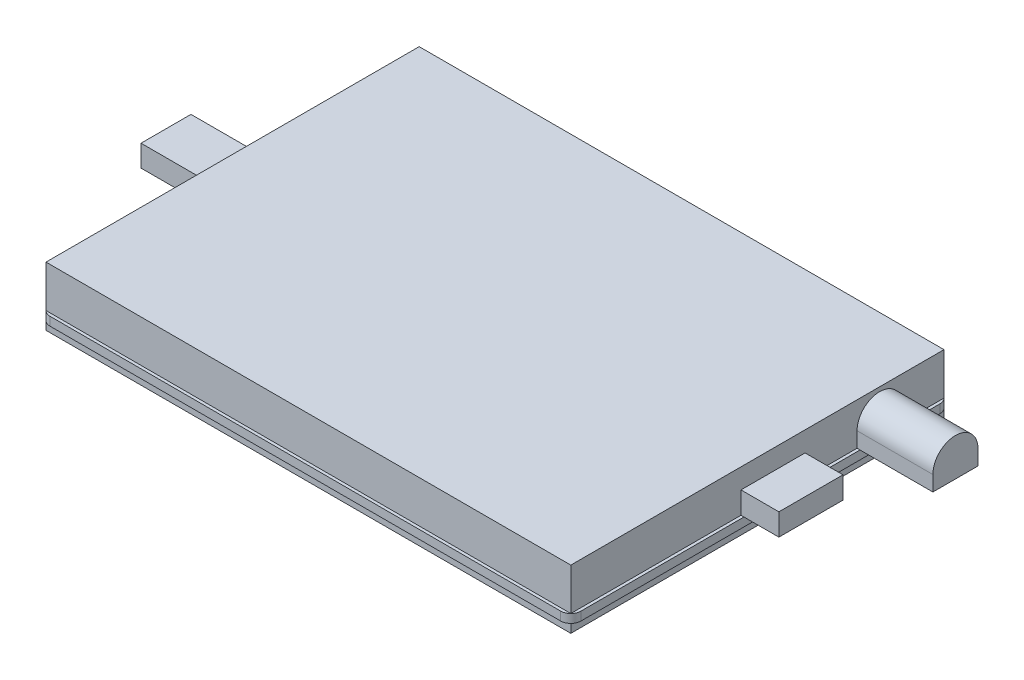
SolidWorks part; units mm, degrees
ref_plane "Plan de face" through (0, 0, 0) normal (0, 0, 1) x (1, 0, 0)
ref_plane "Plan de dessus" through (0, 0, 0) normal (0, 1, 0) x (1, 0, 0)
ref_plane "Plan de droite" through (0, 0, 0) normal (1, 0, 0) x (0, 0, -1)
sketch "Esquisse1" plane through (0, 0, 0) normal (0, 1, 0) x (1, 0, 0)
  line L1 (-50.5, -37.5) -> (50.5, -37.5)
  line L2 (-52.5, -35.5) -> (-52.5, 35.5)
  line L3 (-50.5, 37.5) -> (50.5, 37.5)
  line L4 (52.5, -35.5) -> (52.5, 35.5)
  line L5 (-52.5, -37.5) -> (52.5, 37.5) construction
  line L6 (-52.5, 37.5) -> (52.5, -37.5) construction
  arc A0 (50.5, 37.5) -> (52.5, 35.5) centre (50.5, 35.5) cw
  arc A1 (50.5, -37.5) -> (52.5, -35.5) centre (50.5, -35.5) ccw
  arc A2 (-50.5, -37.5) -> (-52.5, -35.5) centre (-50.5, -35.5) cw
  arc A3 (-52.5, 35.5) -> (-50.5, 37.5) centre (-50.5, 35.5) cw
  point P0 (0, 0)
  dimension "D3" = 2
  dimension "D1" = 75
  dimension "D2" = 105
extrude "FormePCB" add sketch "Esquisse1" along normal blind 1.7
sketch "Esquisse3" plane through (0, 0, 0) normal (0, 1, 0) x (1, 0, 0)
  line L0 (60.2106, 0) -> (-60.2106, 0) construction
  line L1 (0, 42.1093) -> (0, -42.1093) construction
  circle A0 centre (48, 33) radius 2
  circle A1 centre (48, -33) radius 2
  circle A2 centre (-48, 33) radius 2
  circle A3 centre (-48, -33) radius 2
  dimension "D3" = 4
  dimension "D1" = 33
  dimension "D2" = 48
extrude "PaternTrouPCB" cut sketch "Esquisse3" along normal through all
sketch "Esquisse4" plane through (0, 0, 0) normal (0, 1, 0) x (1, 0, 0)
  line L1 (-51.9142, -36.9142) -> (51.9142, -36.9142)
  line L2 (-51.9142, -36.9142) -> (-51.9142, 36.9142)
  line L3 (-51.9142, 36.9142) -> (51.9142, 36.9142)
  line L4 (51.9142, -36.9142) -> (51.9142, 36.9142)
  line L5 (-51.9142, -36.9142) -> (51.9142, 36.9142) construction
  line L6 (-51.9142, 36.9142) -> (51.9142, -36.9142) construction
  arc A0 (52.5, 35.5) -> (50.5, 37.5) centre (50.5, 35.5) ccw construction
  point P0 (0, 0)
extrude "EspaceComposante" add sketch "Esquisse4" along normal blind 10 and the other way blind 1.7 separate body
sketch "Esquisse5" plane through (51.9142, 0, 0) normal (1, 0, 0) x (0, 0, -1)
  line L1 (-3.2459, 6.0441) -> (9.4285, 6.0441)
  line L2 (-3.2459, 6.0441) -> (-3.2459, 1.7)
  line L3 (-3.2459, 1.7) -> (9.4285, 1.7)
  line L4 (9.4285, 6.0441) -> (9.4285, 1.7)
  line L13 (-35.5, 1.7) -> (35.5, 1.7) construction
extrude "EspaceSwitch" add sketch "Esquisse5" along normal blind 7.5
sketch "Esquisse6" plane through (51.9142, 0, 0) normal (1, 0, 0) x (0, 0, -1)
  line L0 (19.7174, 1.7) -> (28.6437, 1.7)
  line L1 (-35.5, 1.7) -> (35.5, 1.7) construction
  line L2 (28.6437, 1.7) -> (28.6437, 4.6993)
  line L3 (19.7174, 4.6993) -> (19.7174, 1.7)
  arc A0 (28.6437, 4.6993) -> (19.7174, 4.6993) centre (24.1806, 4.6993) ccw
extrude "EspacePower" add sketch "Esquisse6" along normal blind 15
sketch "Esquisse7" plane through (-51.9142, 0, 0) normal (-1, 0, 0) x (0, 0, 1)
  line L0 (-6.7652, 1.7) -> (3.1157, 1.7)
  line L1 (-35.5, 1.7) -> (35.5, 1.7) construction
  line L2 (3.1157, 1.7) -> (3.1157, 5.969)
  line L3 (3.1157, 5.969) -> (-6.7652, 5.969)
  line L4 (-6.7652, 5.969) -> (-6.7652, 1.7)
extrude "EspaceUSB" add sketch "Esquisse7" along normal blind 15
